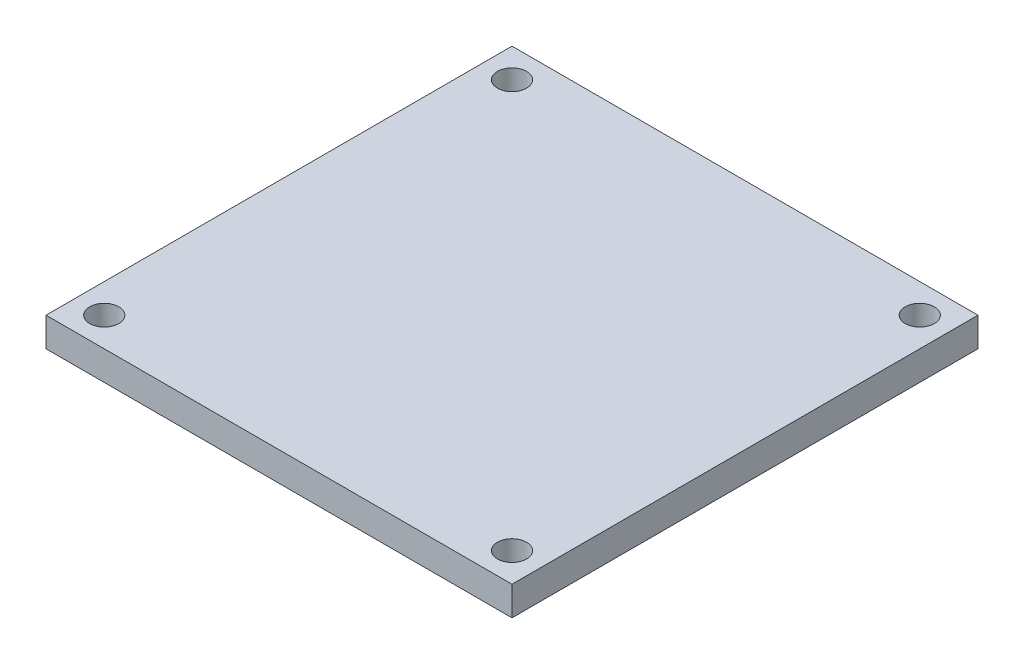
SolidWorks part; units mm, degrees
ref_plane "Front Plane" through (0, 0, 0) normal (0, 0, 1) x (1, 0, 0)
ref_plane "Top Plane" through (0, 0, 0) normal (0, 1, 0) x (1, 0, 0)
ref_plane "Right Plane" through (0, 0, 0) normal (1, 0, 0) x (0, 0, -1)
sketch "Sketch1" plane through (0, 0, 0) normal (0, 1, 0) x (1, 0, 0)
  line L1 (-25.4, 25.4) -> (25.4, 25.4)
  line L2 (-25.4, 25.4) -> (-25.4, -25.4)
  line L3 (-25.4, -25.4) -> (25.4, -25.4)
  line L4 (25.4, 25.4) -> (25.4, -25.4)
  line L5 (-25.4, 25.4) -> (25.4, -25.4) construction
  line L6 (-25.4, -25.4) -> (25.4, 25.4) construction
  point P0 (0, 0)
  dimension "D1" = 50.8
  dimension "D2" = 50.8
extrude "Boss-Extrude1" add sketch "Sketch1" along normal blind 3.175
sketch "Sketch2" plane through (0, 3.175, 0) normal (0, 1, 0) x (1, 0, 0)
  line L0 (0, 25.4) -> (0, -25.4) construction
  line L1 (25.4, 25.4) -> (-25.4, 25.4) construction
  line L2 (-25.4, -25.4) -> (25.4, -25.4) construction
  line L3 (-25.4, 0) -> (25.4, 0) construction
  line L4 (-25.4, 25.4) -> (-25.4, -25.4) construction
  line L5 (25.4, -25.4) -> (25.4, 25.4) construction
  circle A0 centre (-22.225, -22.225) radius 1.5875
  circle A1 centre (22.225, -22.225) radius 1.5875
  circle A2 centre (22.225, 22.225) radius 1.5875
  circle A3 centre (-22.225, 22.225) radius 1.5875
  dimension "D1" = 3.175
  dimension "D2" = 3.175
  dimension "D3" = 3.175
extrude "Cut-Extrude1" cut sketch "Sketch2" against normal through all
